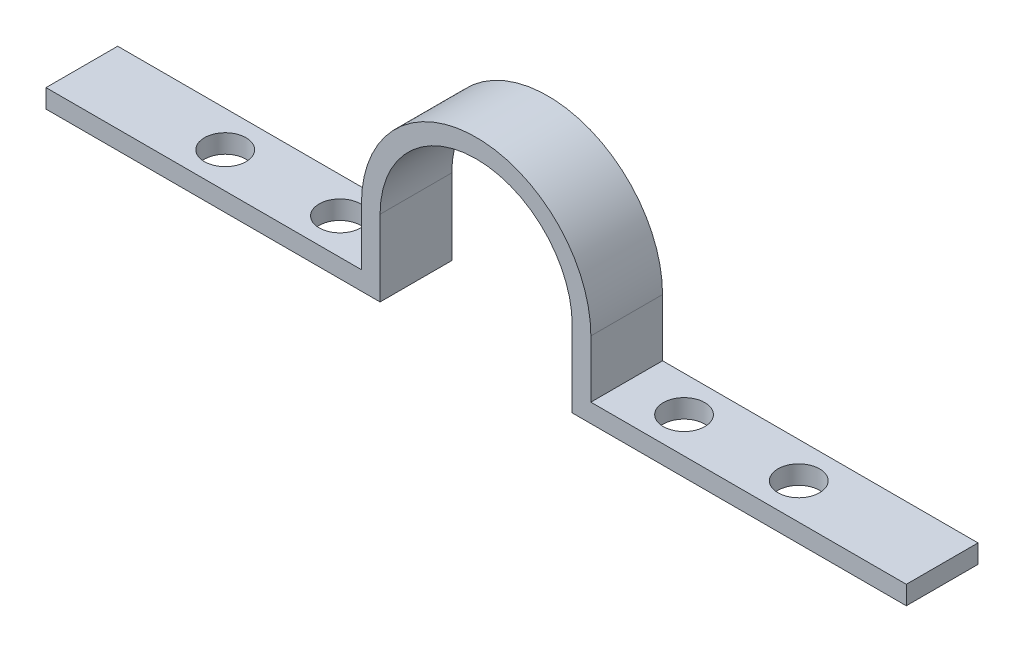
SolidWorks part; units mm, degrees
ref_plane "Alzado" through (0, 0, 0) normal (0, 0, 1) x (1, 0, 0)
ref_plane "Planta" through (0, 0, 0) normal (0, 1, 0) x (1, 0, 0)
ref_plane "Vista lateral" through (0, 0, 0) normal (1, 0, 0) x (0, 0, -1)
sketch "Sketch1" plane through (0, 0, 0) normal (0, 0, 1) x (1, 0, 0)
  line L1 (55, 0) -> (-55, 0) construction
  line L2 (150, 0) -> (150, 6.5)
  line L3 (150, 6.5) -> (40, 6.5)
  line L4 (-150, 6.5) -> (-150, 0)
  line L5 (0, -55) -> (0, 55) construction
  line L9 (-40, 6.5) -> (-150, 6.5)
  line L11 (-40, 26.5) -> (-40, 6.5)
  line L12 (-150, 0) -> (-33.5, 0)
  line L13 (150, 0) -> (33.5, 0)
  line L14 (40, 26.5) -> (40, 6.5)
  line L15 (-33.5, 26.5) -> (-33.5, 0)
  line L16 (33.5, 26.5) -> (33.5, 0)
  arc A0 (40, 26.5) -> (-40, 26.5) centre (0, 26.5) ccw
  arc A1 (33.5, 26.5) -> (-33.5, 26.5) centre (0, 26.5) ccw
  dimension "D5" = 80
  dimension "D6" = 67
  dimension "D1" = 300
  dimension "D2" = 300
  dimension "D3" = 6.5
  dimension "D4" = 150
  dimension "D7" = 20
extrude "Boss-Extrude1" add sketch "Sketch1" along normal blind 25
sketch "Sketch4" plane through (0, 0, 0) normal (0, 1, 0) x (1, 0, 0)
  line L0 (-25.575, 0) -> (25.575, 0) construction
  line L1 (0, -13.75) -> (0, 13.75) construction
  circle A0 centre (-60, -12.5) radius 7.25
  circle A1 centre (-100, -12.5) radius 7.25
  circle A2 centre (60, -12.5) radius 7.25
  circle A3 centre (100, -12.5) radius 7.25
  dimension "D1" = 14.5
  dimension "D2" = 14.5
  dimension "D3" = 12.5
  dimension "D4" = 12.5
  dimension "D5" = 60
  dimension "D6" = 100
extrude "Cut-Extrude1" cut sketch "Sketch4" along normal blind 25
